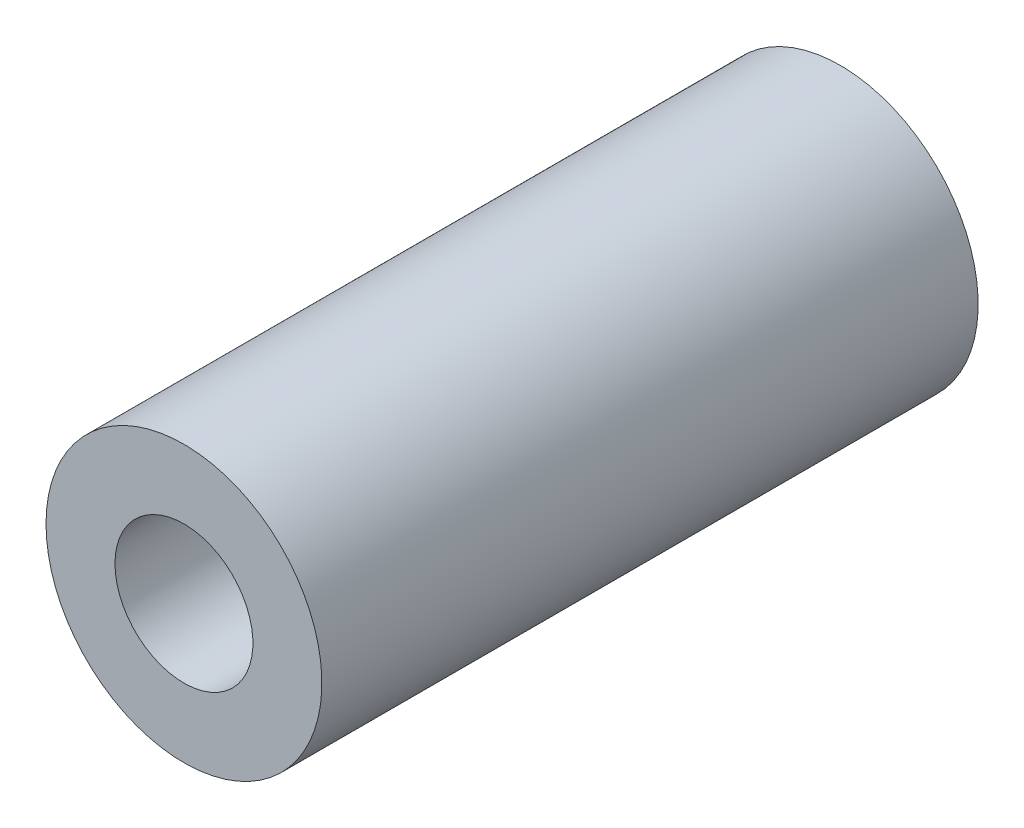
SolidWorks part; units mm, degrees
ref_plane "Front Plane" through (0, 0, 0) normal (0, 0, 1) x (1, 0, 0)
ref_plane "Top Plane" through (0, 0, 0) normal (0, 1, 0) x (1, 0, 0)
ref_plane "Right Plane" through (0, 0, 0) normal (1, 0, 0) x (0, 0, -1)
sketch "Sketch1" plane through (0, 0, 0) normal (0, 0, 1) x (1, 0, 0)
  circle A0 centre (0, 0) radius 6.35
  circle A1 centre (0, 0) radius 3.175
  dimension "D1" = 12.7
  dimension "D2" = 6.35
extrude "Boss-Extrude1" add sketch "Sketch1" along normal mid plane 30.2133
